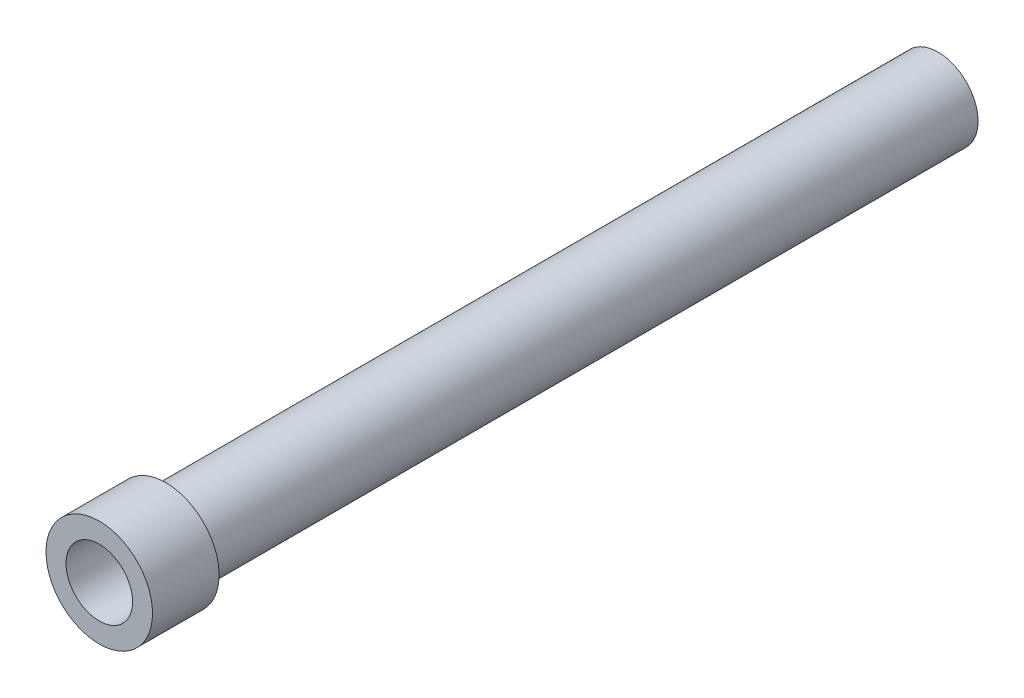
SolidWorks part; units mm, degrees
material "3.3547 (EN-AW 5083)"
ref_plane "Ebene vorne" through (0, 0, 0) normal (0, 0, 1) x (1, 0, 0)
ref_plane "Ebene oben" through (0, 0, 0) normal (0, 1, 0) x (1, 0, 0)
ref_plane "Ebene rechts" through (0, 0, 0) normal (1, 0, 0) x (0, 0, -1)
sketch "Skizze1" plane through (0, 0, 0) normal (0, 0, 1) x (1, 0, 0)
  circle A0 centre (-21.2024, 3.9585) radius 4
extrude "Aufsatz-Linear austragen1" add sketch "Skizze1" along normal blind 63
sketch "Skizze2" plane through (0, 0, 63) normal (0, 0, 1) x (1, 0, 0)
  circle A0 centre (-21.2024, 3.9585) radius 2.5
extrude "Schnitt-Linear austragen1" cut sketch "Skizze2" against normal blind 27
sketch "Skizze3" plane through (0, 0, 0) normal (0, 0, -1) x (-1, 0, 0)
  circle A0 centre (21.2024, 3.9585) radius 12.7694
  circle A1 centre (21.2024, 3.9585) radius 3
extrude "Schnitt-Linear austragen2" cut sketch "Skizze3" against normal blind 58
